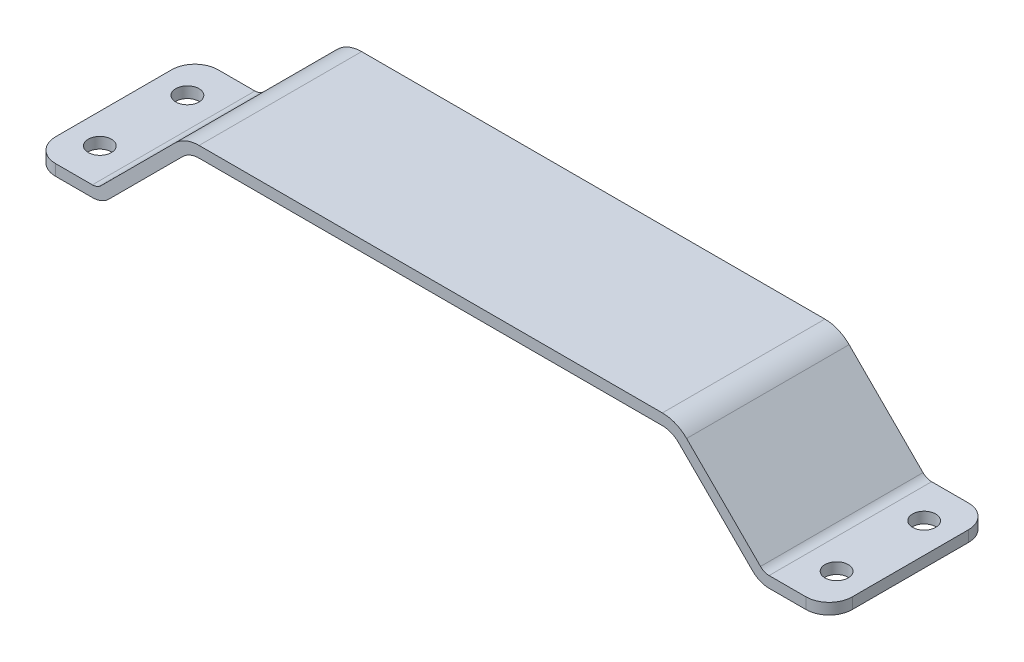
SolidWorks part; units mm, degrees
material "moto_black"
ref_plane "Front Plane" through (0, 0, 0) normal (0, 0, 1) x (1, 0, 0)
ref_plane "Top Plane" through (0, 0, 0) normal (0, 1, 0) x (1, 0, 0)
ref_plane "Right Plane" through (0, 0, 0) normal (1, 0, 0) x (0, 0, -1)
sketch "Sketch1" plane through (0, 0, 0) normal (0, 0, 1) x (1, 0, 0)
  line L0 (-106.8351, 12.0388) -> (-138.6549, -19.781)
  line L5 (-145.726, -22.7099) -> (-171.5838, -22.7099)
  line L6 (12.5816, 19.7277) -> (-99.764, 19.7277)
  line L7 (12.5816, 14.9677) -> (-99.764, 14.9677)
  line L8 (-110.2009, 15.4046) -> (-142.0207, -16.4152)
  line L9 (-145.726, -17.9499) -> (-171.5838, -17.9499)
  line L10 (-171.5838, -17.9499) -> (-171.5838, -22.7099)
  line L11 (0, 0) -> (0, -7.765)
  line L12 (-133.0799, -14.206) -> (-133.0799, -22.8611)
  line L14 (171.5838, -17.9499) -> (171.5838, -22.7099)
  line L15 (145.726, -17.9499) -> (171.5838, -17.9499)
  line L16 (145.726, -22.7099) -> (171.5838, -22.7099)
  line L17 (110.2009, 15.4046) -> (142.0207, -16.4152)
  line L18 (106.8351, 12.0388) -> (138.6549, -19.781)
  line L19 (12.5816, 19.7277) -> (99.764, 19.7277)
  line L20 (12.5816, 14.9677) -> (99.764, 14.9677)
  line L21 (-133.0799, -22.8611) -> (133.0799, -22.8611)
  line L22 (133.0799, -22.8611) -> (133.0799, -14.206)
  arc A0 (-138.6549, -19.781) -> (-145.726, -22.7099) centre (-145.726, -12.7099) cw
  arc A1 (-106.8351, 12.0388) -> (-99.764, 14.9677) centre (-99.764, 4.9677) cw
  arc A2 (-110.2009, 15.4046) -> (-99.764, 19.7277) centre (-99.764, 4.9677) cw
  arc A3 (-142.0207, -16.4152) -> (-145.726, -17.9499) centre (-145.726, -12.7099) cw
  arc A4 (138.6549, -19.781) -> (145.726, -22.7099) centre (145.726, -12.7099) ccw
  arc A5 (142.0207, -16.4152) -> (145.726, -17.9499) centre (145.726, -12.7099) ccw
  arc A6 (106.8351, 12.0388) -> (99.764, 14.9677) centre (99.764, 4.9677) ccw
  arc A7 (110.2009, 15.4046) -> (99.764, 19.7277) centre (99.764, 4.9677) ccw
  point P0 (0, 0)
  point P9 (-141.5838, -22.7099)
  point P36 (0, -22.8611)
  dimension "D3" = 10
  dimension "D1" = 135
  dimension "D2" = 30
  dimension "D5" = 45
  dimension "D4" = 4.76
extrude "Boss-Extrude1" add sketch "Sketch1" against normal blind 70 contours L17 A7 L19 L6 A2 L8 A3 L9 L10 L5 A0 L0 A1 L7 L20 A6 L18 A4 L16 L14 L15 A5
fillet "Fillet1" radius 10 4 edges at (-171.5838, -20.3299, 0) (-171.5838, -20.3299, -70) (171.5838, -20.3299, -70) (171.5838, -20.3299, 0)
sketch "Sketch2" plane through (0, -17.9499, 0) normal (0, 1, 0) x (1, 0, 0)
  line L4 (171.5838, 53.8548) -> (145.726, 53.8548)
  line L5 (171.5838, 35) -> (149.5633, 35)
  line L8 (171.5838, 10) -> (171.5838, 60)
  line L9 (161.5838, 70) -> (145.726, 70)
  line L10 (145.726, 70) -> (145.726, 0)
  line L11 (145.726, 0) -> (161.5838, 0)
  line L12 (171.5838, 10) -> (171.5838, 60)
  line L13 (161.5838, 70) -> (145.726, 70)
  line L14 (145.726, 70) -> (145.726, 0)
  line L15 (145.726, 0) -> (161.5838, 0)
  circle A2 centre (158.6549, 53.8548) radius 5
  circle A3 centre (158.6549, 16.1452) radius 5
  arc A4 (171.5838, 60) -> (161.5838, 70) centre (161.5838, 60) ccw
  arc A5 (161.5838, 0) -> (171.5838, 10) centre (161.5838, 10) ccw
  arc A6 (171.5838, 60) -> (161.5838, 70) centre (161.5838, 60) ccw
  arc A7 (161.5838, 0) -> (171.5838, 10) centre (161.5838, 10) ccw
  dimension "D2" = 10
  dimension "D1" = 0
extrude "Cut-Extrude1" cut sketch "Sketch2" against normal blind 10 contours L4 A2 | L4 A2 | A3
mirror "Mirror1" about plane through (0, 0, 0) normal (1, 0, 0) of "Cut-Extrude1"
